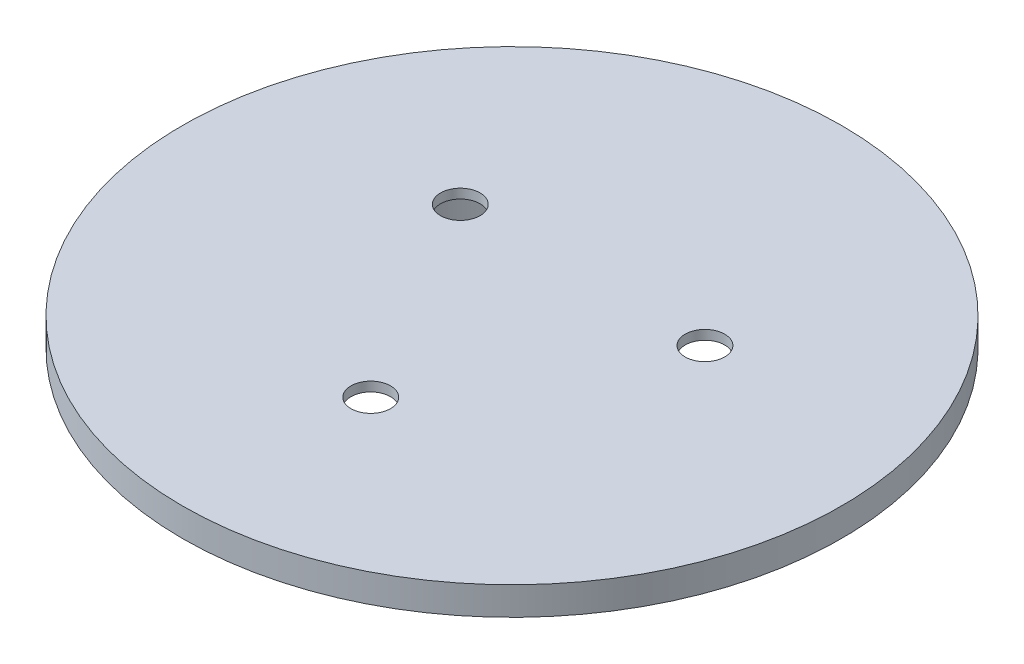
SolidWorks part; units mm, degrees
ref_plane "Front Plane" through (0, 0, 0) normal (0, 0, 1) x (1, 0, 0)
ref_plane "Top Plane" through (0, 0, 0) normal (0, 1, 0) x (1, 0, 0)
ref_plane "Right Plane" through (0, 0, 0) normal (1, 0, 0) x (0, 0, -1)
sketch "Sketch1" plane through (0, 0, 0) normal (0, 1, 0) x (1, 0, 0)
  circle A0 centre (0, 0) radius 25
  dimension "D1" = 50
extrude "Boss-Extrude1" add sketch "Sketch1" along normal blind 4
sketch "Sketch2" plane through (0, 4, 0) normal (0, 1, 0) x (1, 0, 0)
  circle A0 centre (0, 0) radius 35
  dimension "D1" = 70
extrude "Boss-Extrude2" add sketch "Sketch2" along normal blind 3
sketch "Sketch3" plane through (0, 0, 0) normal (0, -1, 0) x (1, 0, 0)
  circle A0 centre (0, 0) radius 20.05
  dimension "D1" = 40.1
extrude "Cut-Extrude1" cut sketch "Sketch3" against normal blind 6
sketch "Sketch4" plane through (0, 6, 0) normal (0, -1, 0) x (1, 0, 0)
  line L0 (0, 0) -> (0, 15) construction
  line L1 (0, 0) -> (12.9904, -7.5) construction
  line L2 (0, 0) -> (-12.9904, -7.5) construction
  circle A0 centre (0, 0) radius 15 construction
  circle A1 centre (0, 0) radius 20.05
  circle A2 centre (0, 0) radius 20.05
  circle A3 centre (0, 15) radius 2.1
  circle A4 centre (-12.9904, -7.5) radius 2.1
  circle A5 centre (12.9904, -7.5) radius 2.1
  dimension "D2" = 30
  dimension "D5" = 4.2
  dimension "D3" = 120
  dimension "D4" = 120
  dimension "D1" = 0
extrude "Cut-Extrude2" cut sketch "Sketch4" against normal up to next contours A0 | A3 | A4 | A5
